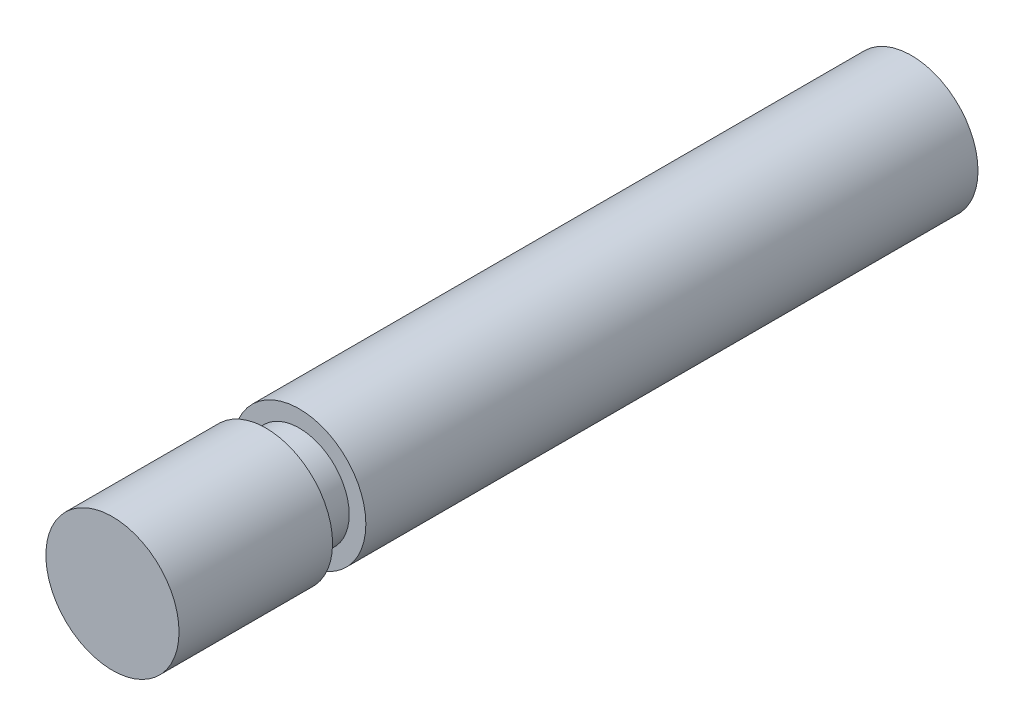
SolidWorks part; units mm, degrees
ref_plane "Front Plane" through (0, 0, 0) normal (0, 0, 1) x (1, 0, 0)
ref_plane "Top Plane" through (0, 0, 0) normal (0, 1, 0) x (1, 0, 0)
ref_plane "Right Plane" through (0, 0, 0) normal (1, 0, 0) x (0, 0, -1)
sketch "Sketch1" plane through (0, 0, 0) normal (1, 0, 0) x (0, 0, -1)
  line L0 (0, 0) -> (0, 50)
  line L1 (0, 50) -> (115.3, 50)
  line L5 (234.4, 50) -> (542.732, 50)
  line L6 (0, 0) -> (600, 0)
  line L7 (600, 0) -> (600, 50)
  line L8 (600, 50) -> (542.732, 50)
  line L9 (115.3, 50) -> (115.3, 37.5)
  line L10 (115.3, 37.5) -> (140.3, 37.5)
  line L11 (140.3, 37.5) -> (140.3, 50)
  line L16 (234.4, 50) -> (209.4, 50)
  line L17 (140.3, 50) -> (209.4, 50)
  dimension "D1" = 50
  dimension "D2" = 209.4
  dimension "D5" = 600
  dimension "D6" = 115.3
  dimension "D7" = 25
revolve "Revolve1" add sketch "Sketch1" angle 360 about L6
